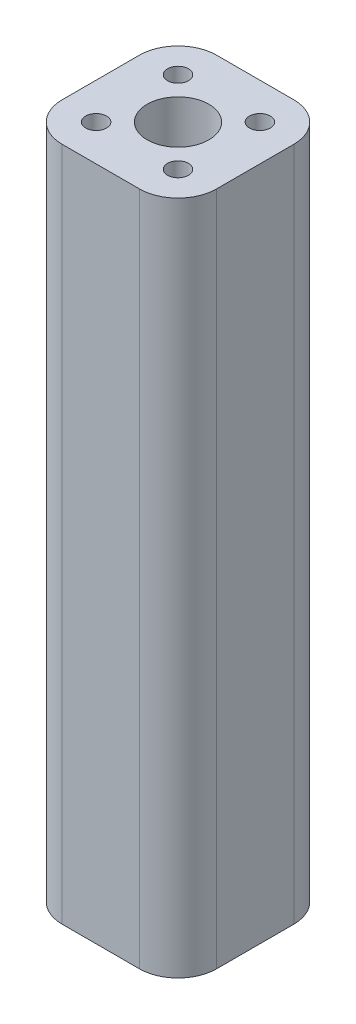
SolidWorks part; units mm, degrees
material "ABS"
ref_plane "Front Plane" through (0, 0, 0) normal (0, 0, 1) x (1, 0, 0)
ref_plane "Top Plane" through (0, 0, 0) normal (0, 1, 0) x (1, 0, 0)
ref_plane "Right Plane" through (0, 0, 0) normal (1, 0, 0) x (0, 0, -1)
sketch "Sketch1" plane through (0, 0, 0) normal (0, 1, 0) x (1, 0, 0)
  line L1 (-20, -20) -> (20, -20)
  line L2 (-20, -20) -> (-20, 20)
  line L3 (-20, 20) -> (20, 20)
  line L4 (20, -20) -> (20, 20)
  line L5 (-20, -20) -> (20, 20) construction
  line L6 (-20, 20) -> (20, -20) construction
  circle A0 centre (-10.6066, 10.6066) radius 2.7
  circle A1 centre (10.6066, 10.6066) radius 2.7
  circle A2 centre (10.6066, -10.6066) radius 2.7
  circle A3 centre (-10.6066, -10.6066) radius 2.7
  circle A4 centre (0, 0) radius 8
  point P0 (0, 0)
  point P17 (0, 0)
  dimension "D4" = 5.4
  dimension "D6" = 16
  dimension "D1" = 40
  dimension "D2" = 40
  dimension "D3" = 15
  dimension "D5" = 4
extrude "Boss-Extrude1" add sketch "Sketch1" along normal blind 175
fillet "Fillet1" radius 10 4 edges at (-20, 87.5, -20) (20, 87.5, -20) (20, 87.5, 20) (-20, 87.5, 20)
